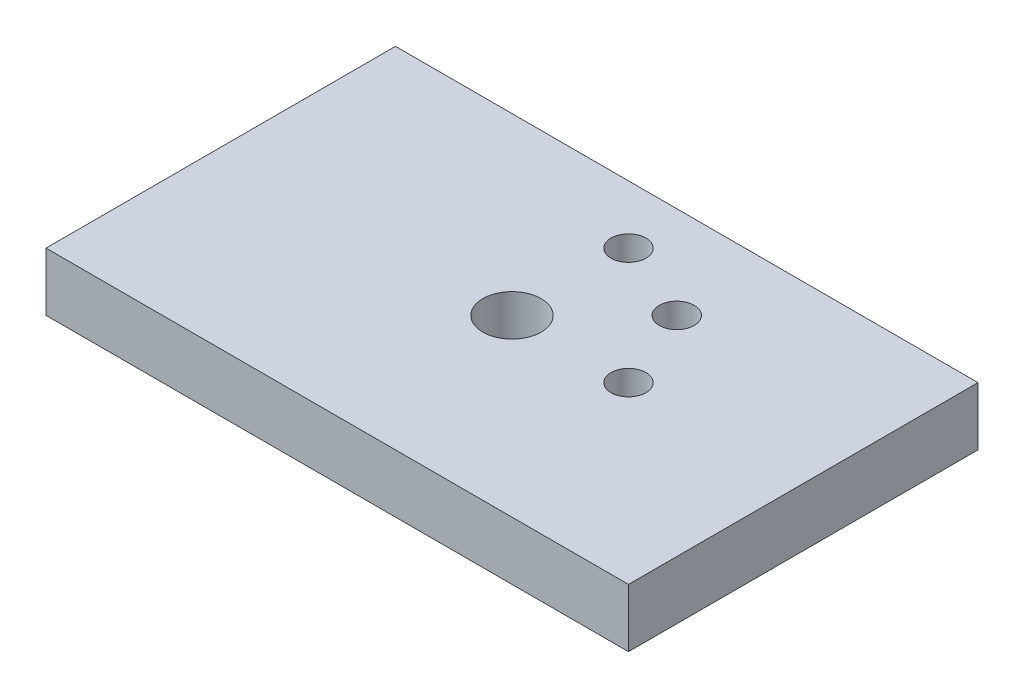
SolidWorks part; units mm, degrees
ref_plane "前视基准面" through (0, 0, 0) normal (0, 0, 1) x (1, 0, 0)
ref_plane "上视基准面" through (0, 0, 0) normal (0, 1, 0) x (1, 0, 0)
ref_plane "右视基准面" through (0, 0, 0) normal (1, 0, 0) x (0, 0, -1)
other "Configuration Table"
sketch "草图1" plane through (0, 0, 0) normal (0, 1, 0) x (1, 0, 0)
  line L1 (-50, -30) -> (50, -30)
  line L2 (-50, -30) -> (-50, 30)
  line L3 (-50, 30) -> (50, 30)
  line L4 (50, -30) -> (50, 30)
  line L5 (-50, -30) -> (50, 30) construction
  line L6 (-50, 30) -> (50, -30) construction
  point P0 (0, 0)
extrude "凸台-拉伸1" add sketch "草图1" along normal blind 10
sketch "草图2" plane through (0, 0, 0) normal (0, 1, 0) x (1, 0, 0)
  circle A0 centre (0, 0) radius 5
extrude "切除-拉伸1" cut sketch "草图2" along normal blind 20
sketch "草图3" plane through (0, 0, 0) normal (0, 1, 0) x (1, 0, 0)
  circle A0 centre (20, 0) radius 3
extrude "切除-拉伸2" cut sketch "草图3" along normal blind 20
pattern_circular "阵列(圆周)1" count 3 over 90 about axis through (0, 0, 0) along (0, 1, 0) of "切除-拉伸2"
